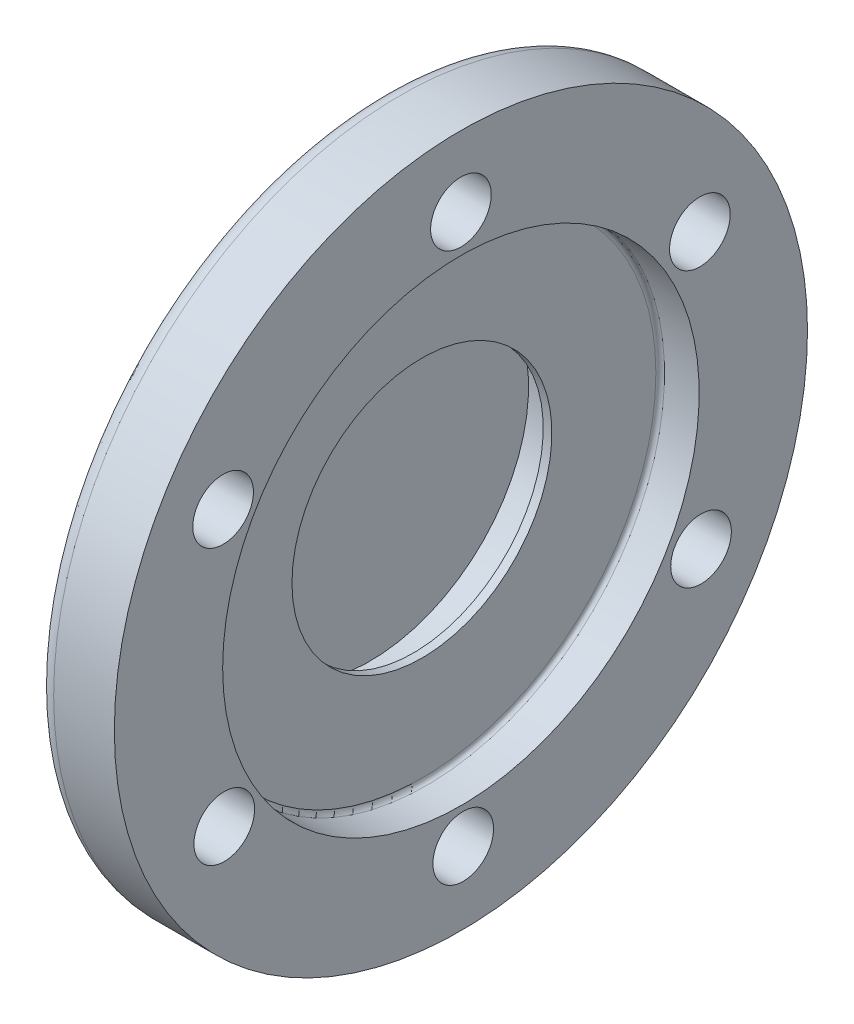
SolidWorks part; units mm, degrees
ref_plane "Front Plane" through (0, 0, 0) normal (0, 0, 1) x (1, 0, 0)
ref_plane "Top Plane" through (0, 0, 0) normal (0, 1, 0) x (1, 0, 0)
ref_plane "Right Plane" through (0, 0, 0) normal (1, 0, 0) x (0, 0, -1)
sketch "Sketch1" plane through (0, 0, 0) normal (0, 1, 0) x (1, 0, 0)
  line L0 (-3.252, 30) -> (-1.252, 30)
  line L1 (-1.252, 30) -> (-1.252, 55)
  line L2 (-1.252, 55) -> (7.748, 55)
  line L3 (7.748, 55) -> (7.748, 60)
  line L7 (-10.2556, 80) -> (-10.2556, 48)
  line L8 (-13.2556, 45) -> (-18.1652, 45)
  line L11 (-3.252, 36.6188) -> (-3.252, 30)
  line L12 (7.748, 60) -> (-6.2556, 60)
  line L13 (-6.2556, 60) -> (-6.2556, 80)
  line L14 (-6.2556, 80) -> (-10.2556, 80)
  line L16 (0, 0) -> (11.072, 0) construction
  line L17 (-18.1652, 45) -> (-18.1652, 0)
  line L18 (-3.252, 36.6188) -> (-13.2556, 36.6188)
  line L19 (-13.2556, 36.6188) -> (-13.2556, 0)
  line L20 (-13.2556, 0) -> (-18.1652, 0)
  arc A0 (-10.2556, 48) -> (-13.2556, 45) centre (-13.2556, 48) cw
  point P3 (-1.252, 50)
  point P8 (-0.9815, 50)
  point P18 (-10.2556, 45)
  point P21 (-1.252, 55)
  dimension "D11" = 3
  dimension "D1" = 2
  dimension "D2" = 25
  dimension "D3" = 80
  dimension "D4" = 30
  dimension "D6" = 9
  dimension "D7" = 5
  dimension "D9" = 4
  dimension "D10" = 35
revolve "Revolve1" add sketch "Sketch1" angle 360 about L16
sketch "Sketch2" plane through (0, 0, 0) normal (0, 1, 0) x (1, 0, 0)
  line L2 (7.748, 60) -> (-6.2556, 60) construction
  line L3 (7.748, 80) -> (7.748, 60)
  line L4 (7.748, 60) -> (-6.2556, 60)
  line L5 (-6.2556, 80) -> (7.748, 80)
  line L6 (-6.2556, 60) -> (-6.2556, 80)
  line L8 (0, 0) -> (-67.6972, 0) construction
  line L9 (7.748, -60) -> (7.748, 60) construction
  line L10 (-6.2556, -80) -> (-6.2556, 80) construction
  point P3 (5.7472, 79.2375)
  point P4 (-6.2556, 55)
  point P6 (6.2472, 79.2375)
  point P10 (6.7472, 80.1181)
  dimension "D1" = 80
revolve "Revolve2" add sketch "Sketch2" angle 360 about L8
sketch "Sketch3" plane through (-10.2556, 0, 0) normal (-1, 0, 0) x (0, 0, 1)
  line L0 (0, 79.3812) -> (0, 48) construction
  circle A0 centre (0, 0) radius 48 construction
  circle A1 centre (0, 0) radius 48
  circle A3 centre (0, 0) radius 79.3812
  circle A4 centre (0, 0) radius 63.6906
  point P9 (0, 63.6906)
hole_wizard "M16x2.0 Tapped Hole1" positions "Sketch4" profile "Sketch5" tap size "M16x2.0" standard "ANSI Metric" end condition through all
sketch "Sketch4" plane through (-10.2556, 0, 0) normal (-1, 0, 0) x (0, 0, 1)
  circle A0 centre (0, 0) radius 63.6906 construction
  point P0 (0, 63.6906)
  point P8 (54.8897, 31.6906)
  point P9 (54.6218, -31.8453)
  point P10 (-0.5359, -63.3812)
  point P11 (-55.4256, -31.3812)
  point P12 (-55.1577, 32.1547)
  dimension "D1" = 6
sketch "Sketch5" plane through (-10.2556, 63.6906, 0) normal (0, 1, 0) x (0, 0, 1)
  line L0 (0, 0) -> (0, 18.0037)
  line L1 (0, 18.0037) -> (7, 18.0037)
  line L2 (7, 18.0037) -> (7, 0)
  line L5 (7, 0) -> (0, 0)
  line L11 (0, -6.35) -> (0, 107.95) construction
  dimension "Thru Tap Drill Dia." = 14
  dimension "Thru Tap Drill Depth" = 18.0037
cosmetic thread "Hole Thread1" parameters "D2"=16
cosmetic thread "Hole Thread2" parameters "D2"=16
cosmetic thread "Hole Thread3" parameters "D2"=16
cosmetic thread "Hole Thread4" parameters "D2"=16
cosmetic thread "Hole Thread5" parameters "D2"=16
cosmetic thread "Hole Thread6" parameters "D2"=16
fillet "Fillet4" radius 4 1 edges at (-10.2556, 0, 80)
fillet "Fillet5" radius 1 1 edges at (-1.252, 0, 55)
